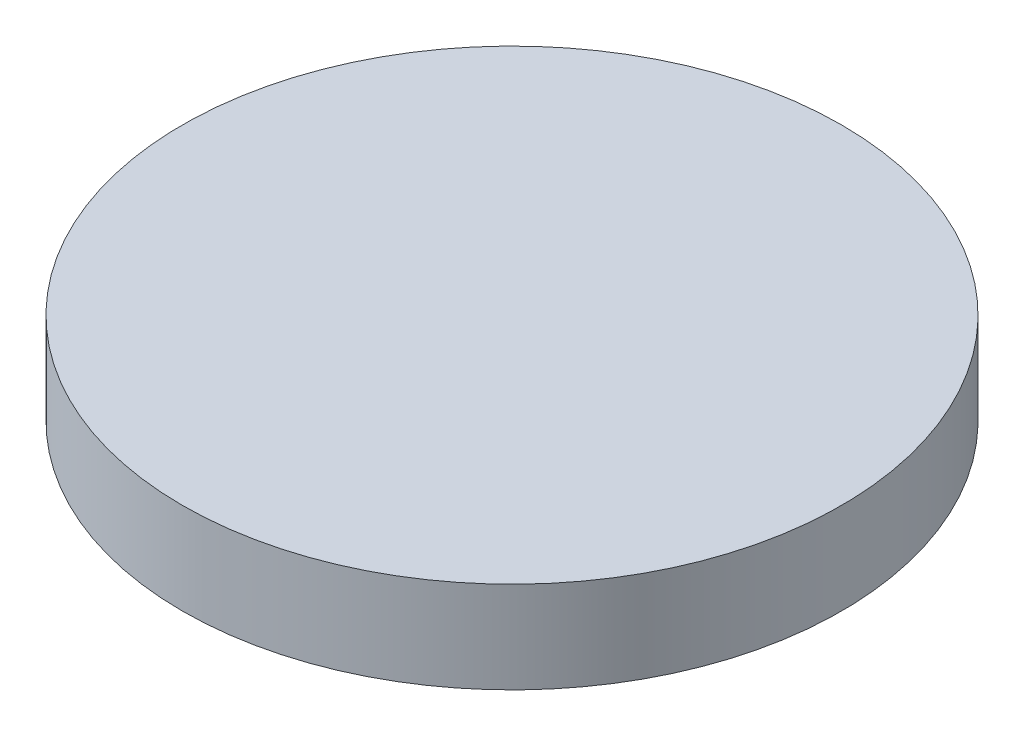
SolidWorks part; units mm, degrees
ref_plane "Front Plane" through (0, 0, 0) normal (0, 0, 1) x (1, 0, 0)
ref_plane "Top Plane" through (0, 0, 0) normal (0, 1, 0) x (1, 0, 0)
ref_plane "Right Plane" through (0, 0, 0) normal (1, 0, 0) x (0, 0, -1)
sketch "Sketch1" plane through (0, 0, 0) normal (0, 1, 0) x (1, 0, 0)
  circle A0 centre (4.9997, -4.9619) radius 11.43
  dimension "D1" = 22.86
extrude "Boss-Extrude1" add sketch "Sketch1" along normal blind 3.175
